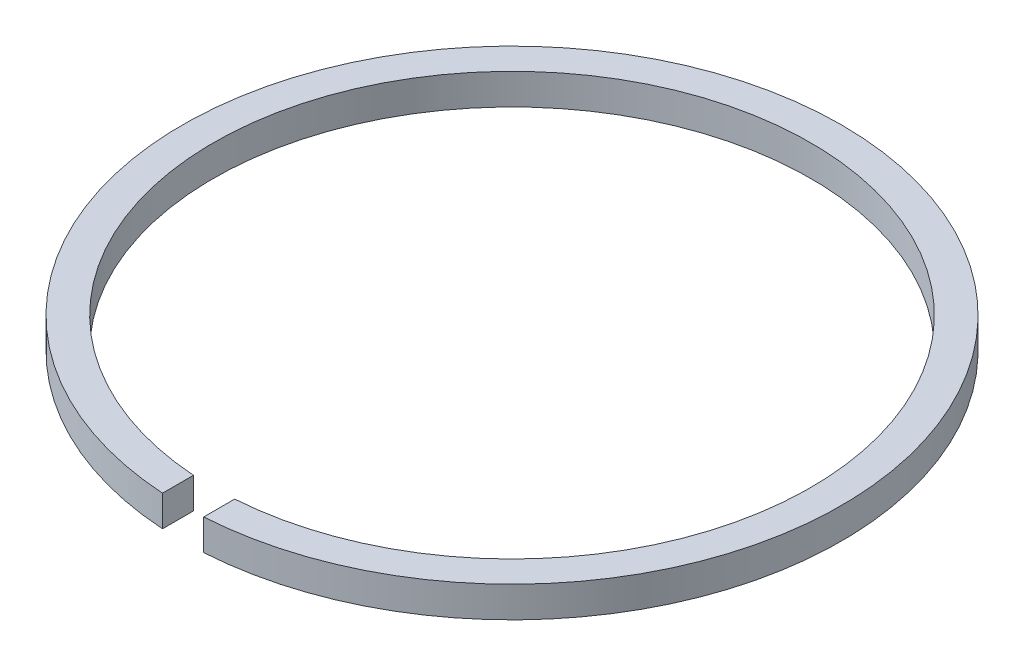
SolidWorks part; units mm, degrees
material "Chrome Stainless Steel"
ref_plane "Front Plane" through (0, 0, 0) normal (0, 0, 1) x (1, 0, 0)
ref_plane "Top Plane" through (0, 0, 0) normal (0, 1, 0) x (1, 0, 0)
ref_plane "Right Plane" through (0, 0, 0) normal (1, 0, 0) x (0, 0, -1)
sketch "Sketch1" plane through (0, 0, 0) normal (0, 1, 0) x (1, 0, 0)
  line L1 (-1, -14.4655) -> (-1, -15.9687)
  line L2 (1, -14.4655) -> (1, -15.9687)
  arc A0 (1, -15.9687) -> (-1, -15.9687) centre (0, 0) ccw
  arc A1 (1, -14.4655) -> (-1, -14.4655) centre (0, 0) ccw
  dimension "D1" = 32
  dimension "D2" = 29
extrude "Boss-Extrude1" add sketch "Sketch1" along normal blind 1.5 contours A0 L1 A1 L2
